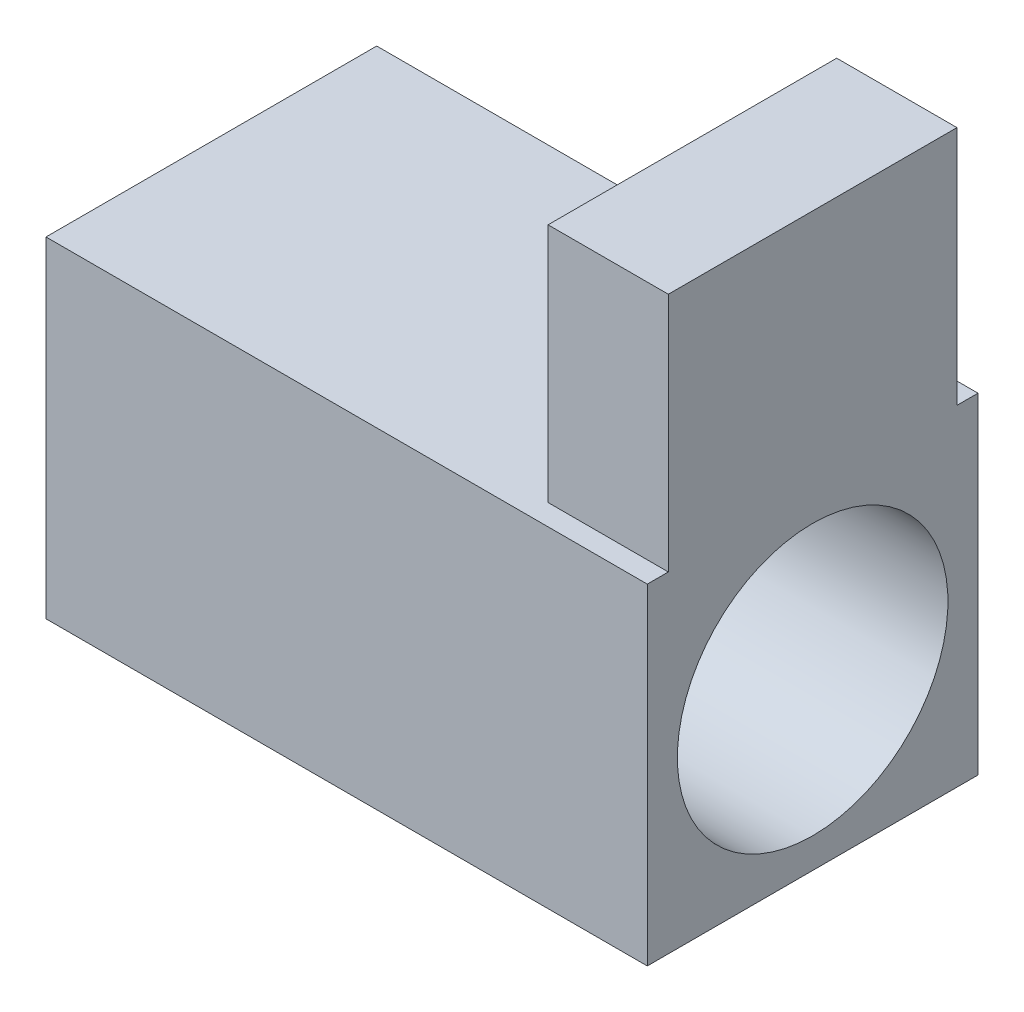
SolidWorks part; units mm, degrees
ref_plane "Front Plane" through (0, 0, 0) normal (0, 0, 1) x (1, 0, 0)
ref_plane "Top Plane" through (0, 0, 0) normal (0, 1, 0) x (1, 0, 0)
ref_plane "Right Plane" through (0, 0, 0) normal (1, 0, 0) x (0, 0, -1)
sketch "Sketch2" plane through (0, 0, 0) normal (0, 0, 1) x (1, 0, 0)
  line L1 (-5, 2.75) -> (5, 2.75)
  line L2 (-5, 2.75) -> (-5, -2.75)
  line L3 (-5, -2.75) -> (5, -2.75)
  line L4 (5, 2.75) -> (5, -2.75)
  line L5 (-5, 2.75) -> (5, -2.75) construction
  line L6 (-5, -2.75) -> (5, 2.75) construction
  point P0 (0, 0)
  dimension "D1" = 10
  dimension "D2" = 5.5
extrude "Boss-Extrude1" add sketch "Sketch2" along normal mid plane 5.5
sketch "Sketch3" plane through (5, 0, 0) normal (1, 0, 0) x (0, 0, -1)
  circle A0 centre (0, 0) radius 2.25
  dimension "D1" = 4.5
extrude "Cut-Extrude1" cut sketch "Sketch3" against normal blind 5
sketch "Sketch4" plane through (0, 2.75, 0) normal (0, 1, 0) x (1, 0, 0)
  line L5 (5, -2.75) -> (5, 2.75) construction
  line L6 (3, 2.4) -> (5, 2.4)
  line L7 (3, 2.4) -> (3, -2.4)
  line L8 (3, -2.4) -> (5, -2.4)
  line L9 (5, 2.4) -> (5, -2.4)
  line L10 (3, 2.4) -> (5, -2.4) construction
  line L11 (3, -2.4) -> (5, 2.4) construction
  line L12 (0, 0) -> (5.0189, 0) construction
  point P0 (4, 0)
  point P4 (3, 0.641)
  dimension "D1" = 2
  dimension "D2" = 4.8
extrude "Boss-Extrude2" add sketch "Sketch4" along normal blind 4
